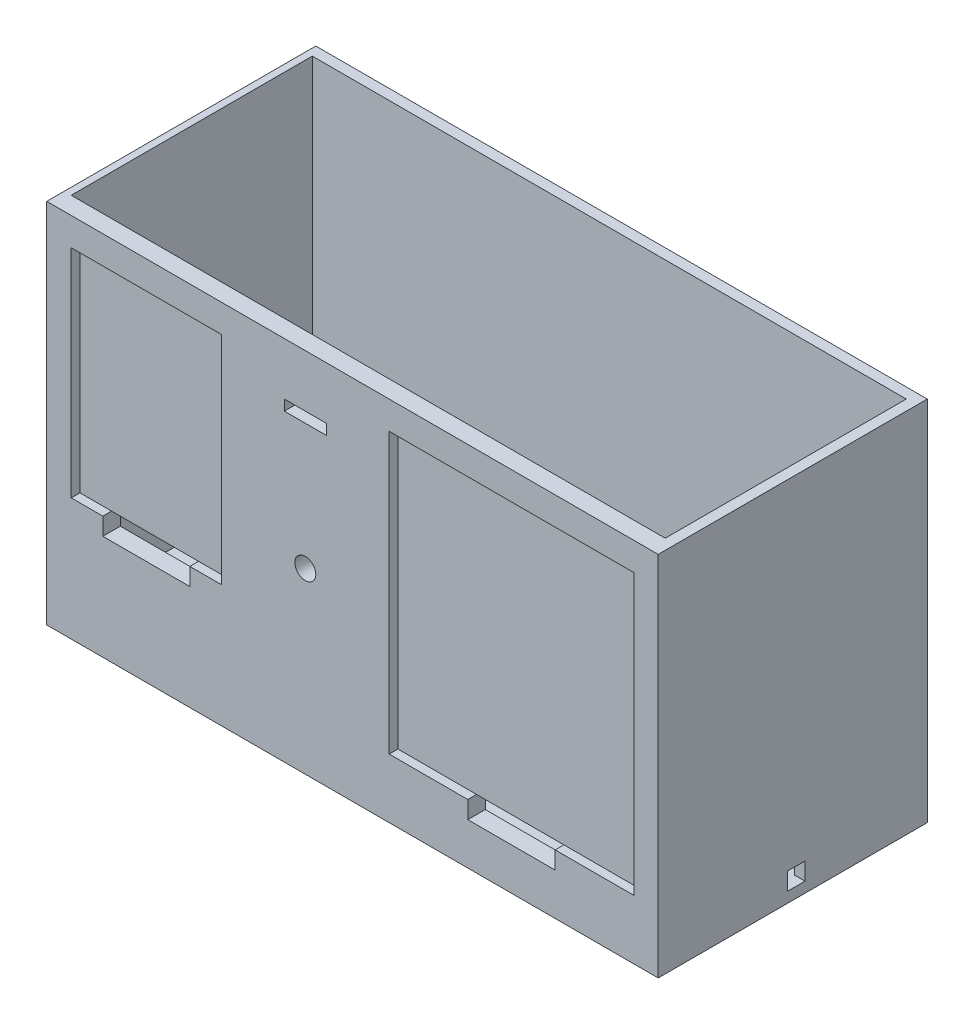
SolidWorks part; units mm, degrees
ref_plane "Front Plane" through (0, 0, 0) normal (0, 0, 1) x (1, 0, 0)
ref_plane "Top Plane" through (0, 0, 0) normal (0, 1, 0) x (1, 0, 0)
ref_plane "Right Plane" through (0, 0, 0) normal (1, 0, 0) x (0, 0, -1)
sketch "Sketch1" plane through (0, 0, 0) normal (0, 1, 0) x (1, 0, 0)
  line L0 (73, 2) -> (73, -75)
  line L5 (73, -75) -> (-102, -75)
  line L6 (-102, 2) -> (-102, -75)
  line L7 (73, 2) -> (-102, 2)
  line L8 (70, -1) -> (70, -70)
  line L9 (70, -70) -> (-100, -70)
  line L10 (-100, -1) -> (-100, -70)
  line L11 (70, -1) -> (-100, -1)
extrude "Boss-Extrude1" add sketch "Sketch1" along normal blind 105
sketch "Sketch2" plane through (0, 0, 0) normal (0, -1, 0) x (-1, 0, 0)
  line L1 (102, -75) -> (-73, -75)
  line L2 (102, -75) -> (102, 2)
  line L3 (102, 2) -> (-73, 2)
  line L4 (-73, -75) -> (-73, 2)
extrude "Boss-Extrude2" add sketch "Sketch2" against normal blind 3
sketch "Sketch3" plane through (0, 0, 75) normal (0, 0, 1) x (1, 0, 0)
  line L0 (66, 105) -> (66, 97) construction
  line L1 (66, 97) -> (66, 17)
  line L3 (66, 17) -> (66, 0) construction
  line L5 (-102, 0) -> (73, 0) construction
  line L6 (66, 97) -> (-4, 97)
  line L7 (-4, 97) -> (-4, 17)
  line L8 (-4, 17) -> (66, 17)
  line L9 (-52, 97) -> (-95, 97)
  line L10 (-95, 97) -> (-95, 35)
  line L11 (-52, 97) -> (-52, 35)
  line L12 (-52, 35) -> (-95, 35)
extrude "Cut-Extrude1" cut sketch "Sketch3" against normal blind 2.5
sketch "Sketch4" plane through (0, 0, 75) normal (0, 0, 1) x (1, 0, 0)
  line L0 (-28, 66) -> (-28, 51) construction
  line L1 (18.5, 17) -> (43.5, 17)
  line L2 (18.5, 17) -> (18.5, 12)
  line L3 (18.5, 12) -> (43.5, 12)
  line L4 (43.5, 17) -> (43.5, 12)
  line L5 (-4, 17) -> (66, 17) construction
  line L7 (-4, 17) -> (66, 17) construction
  line L8 (-85.9518, 35) -> (-61.0482, 35)
  line L9 (-85.9518, 35) -> (-85.9518, 30)
  line L10 (-85.9518, 30) -> (-61.0482, 30)
  line L11 (-61.0482, 35) -> (-61.0482, 30)
  line L12 (-95, 35) -> (-52, 35)
  line L13 (-52, 66) -> (-4, 66) construction
  line L14 (-52, 35) -> (-52, 97) construction
  line L15 (-4, 97) -> (-4, 17) construction
  line L19 (-22, 90) -> (-34, 90)
  line L20 (-22, 90) -> (-22, 87)
  line L21 (-22, 87) -> (-34, 87)
  line L22 (-34, 90) -> (-34, 87)
  line L23 (-22, 90) -> (-34, 87) construction
  line L24 (-22, 87) -> (-34, 90) construction
  circle A0 centre (-28, 51) radius 3
  point P6 (31, 17)
  point P8 (31, 17)
  point P16 (-73.5, 35)
  point P21 (-73.5, 35)
  point P32 (-28, 85.5)
  line M1 (-52, 35) -> (-95, 35)
  line M8 (66, 17) -> (-4, 17)
extrude "Cut-Extrude2" cut sketch "Sketch4" against normal blind 12.5 contours L19 L22 L21 L20 | L11 L9 L10 M1 | L4 L2 L3 M8 | A0
sketch "Sketch5" plane through (0, 0, 1) normal (0, 0, 1) x (1, 0, 0)
  line L0 (-15, 3) -> (-15, 105) construction
  line L1 (-100, 3) -> (70, 3) construction
  line L2 (70, 105) -> (-100, 105) construction
  line L3 (-15, 105) -> (70, 54) construction
  line L4 (70, 105) -> (70, 3) construction
  line L5 (70, 54) -> (-15, 54) construction
  line L6 (-15, 54) -> (27.5, 54) construction
  line L7 (27.5, 54) -> (27.5, 3) construction
  line L8 (27.5, 3) -> (70, 3) construction
  line L10 (39.925, 3) -> (57.575, 3)
  line L11 (39.925, 3) -> (39.925, 21.35)
  line L12 (39.925, 21.35) -> (57.575, 21.35)
  line L13 (57.575, 3) -> (57.575, 21.35)
  point P18 (48.75, 3)
  point P19 (48.75, 3)
extrude "Cut-Extrude3" cut sketch "Sketch5" against normal blind 10
sketch "Sketch6" plane through (70, 0, 0) normal (-1, 0, 0) x (0, 0, 1)
  line L0 (1, 3) -> (70, 3) construction
  line L2 (38, 8) -> (33, 8)
  line L3 (38, 8) -> (38, 3)
  line L4 (38, 3) -> (33, 3)
  line L5 (33, 8) -> (33, 3)
  point P8 (35.5, 3)
  point P9 (35.5, 3)
extrude "Cut-Extrude4" cut sketch "Sketch6" against normal blind 10
